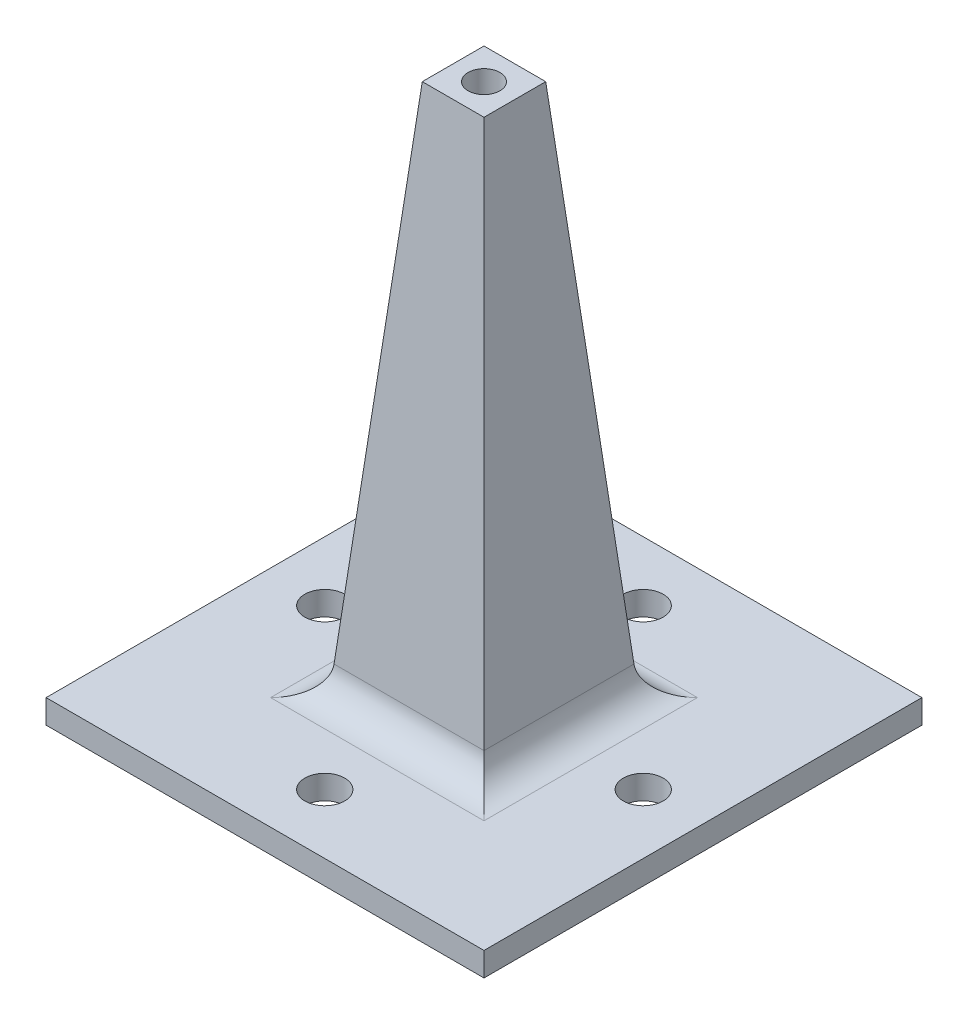
SolidWorks part; units mm, degrees
material "ABS"
ref_plane "Front Plane" through (0, 0, 0) normal (0, 0, 1) x (1, 0, 0)
ref_plane "Top Plane" through (0, 0, 0) normal (0, 1, 0) x (1, 0, 0)
ref_plane "Right Plane" through (0, 0, 0) normal (1, 0, 0) x (0, 0, -1)
sketch "Sketch1" plane through (0, 0, 0) normal (0, 1, 0) x (1, 0, 0)
  line L1 (-10, 10) -> (10, 10)
  line L2 (-10, 10) -> (-10, -10)
  line L3 (-10, -10) -> (10, -10)
  line L4 (10, 10) -> (10, -10)
  line L5 (-10, 10) -> (10, -10) construction
  line L6 (-10, -10) -> (10, 10) construction
  point P0 (0, 0)
  dimension "D1" = 20
  dimension "D2" = 20
extrude "Boss-Extrude1" add sketch "Sketch1" along normal blind 70 draft 5
sketch "Sketch2" plane through (0, 70, 0) normal (0, 1, 0) x (1, 0, 0)
  circle A0 centre (0, 0) radius 2
  dimension "D1" = 4
extrude "Cut-Extrude1" cut sketch "Sketch2" against normal blind 12.5
sketch "Sketch3" plane through (0, 0, 0) normal (0, -1, 0) x (1, 0, 0)
  line L6 (-27.5, 27.5) -> (27.5, 27.5)
  line L10 (-27.5, 27.5) -> (-27.5, -27.5)
  line L11 (-27.5, -27.5) -> (27.5, -27.5)
  line L12 (27.5, 27.5) -> (27.5, -27.5)
  line L13 (-27.5, 27.5) -> (27.5, -27.5) construction
  line L14 (-27.5, -27.5) -> (27.5, 27.5) construction
  point P0 (0, 0)
  dimension "D1" = 55
  dimension "D2" = 55
extrude "Boss-Extrude2" add sketch "Sketch3" against normal blind 3
fillet "Fillet1" radius 4 4 edges at (-9.7375, 3, 0) (0, 3, 9.7375) (9.7375, 3, 0) (0, 3, -9.7375)
sketch "Sketch5" plane through (0, 3, 0) normal (0, 1, 0) x (1, 0, 0)
  line L0 (-27.5, -27.5) -> (-27.5, 27.5) construction
  circle A0 centre (-20, 0) radius 2.5
  circle A1 centre (0, 20) radius 2.5
  circle A2 centre (20, 0) radius 2.5
  circle A3 centre (0, -20) radius 2.5
  point P11 (0, 0)
  dimension "D1" = 5
  dimension "D3" = 7.5
  dimension "D2" = 4
extrude "Cut-Extrude2" cut sketch "Sketch5" against normal blind 10
